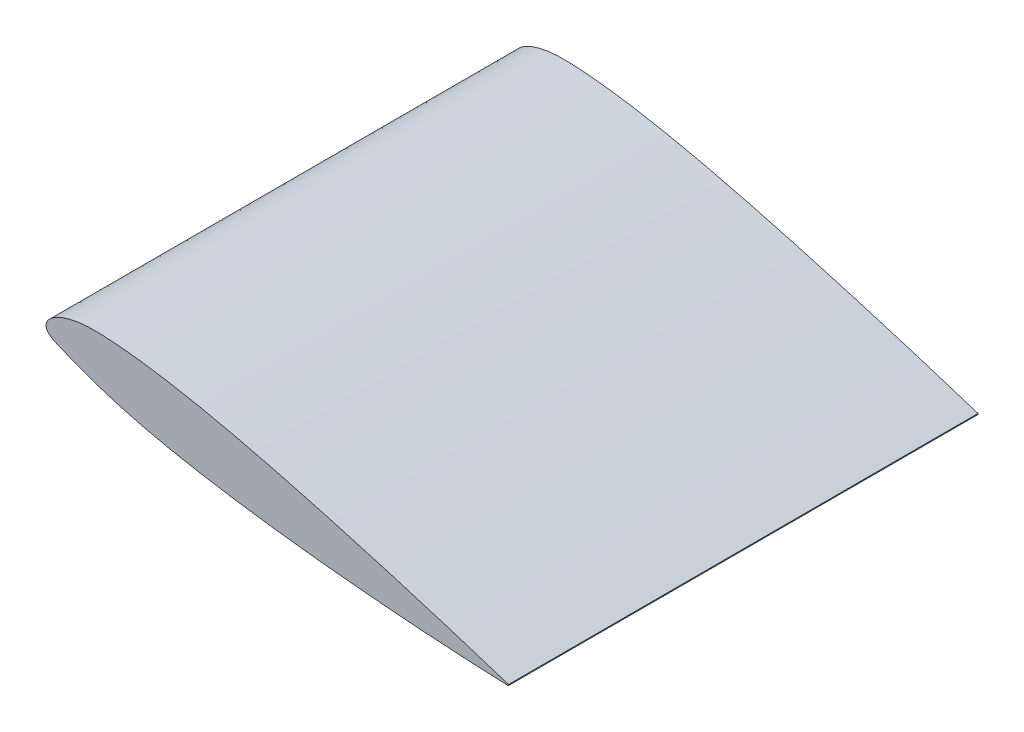
SolidWorks part; units mm, degrees
ref_plane "Płaszczyzna przednia"
ref_plane "Płaszczyzna górna" through (0, 0, 0) normal (0, 1, 0) x (1, 0, 0)
ref_plane "Płaszczyzna prawa" through (0, 0, 0) normal (1, 0, 0) x (0, 0, -1)
curve "Krzywa3"
  spline degree 3 poles (1, 0.0013, 0) (0.9998, 0.0013, 0) (0.9989, 0.0014, 0) (0.9968, 0.0017, 0) (0.9934, 0.0022, 0) (0.9886, 0.0029, 0) (0.9826, 0.0038, 0) (0.9751, 0.0049, 0) (0.9664, 0.0061, 0) (0.9564, 0.0076, 0) (0.9452, 0.0092, 0) (0.9327, 0.0109, 0) (0.9191, 0.0128, 0) (0.9043, 0.0148, 0) (0.8884, 0.017, 0) (0.8714, 0.0192, 0) (0.8535, 0.0216, 0) (0.8346, 0.0241, 0) (0.8147, 0.0266, 0) (0.794, 0.0292, 0) (0.7725, 0.0318, 0) (0.7503, 0.0345, 0) (0.7273, 0.0373, 0) (0.7038, 0.04, 0) (0.6797, 0.0427, 0) (0.6551, 0.0454, 0) (0.6301, 0.0481, 0) (0.6047, 0.0508, 0) (0.5791, 0.0533, 0) (0.5532, 0.0558, 0) (0.5272, 0.0582, 0) (0.5011, 0.0605, 0) (0.475, 0.0626, 0) (0.449, 0.0646, 0) (0.4231, 0.0664, 0) (0.3975, 0.068, 0) (0.3721, 0.0694, 0) (0.347, 0.0706, 0) (0.3224, 0.0715, 0) (0.2982, 0.0722, 0) (0.2746, 0.0726, 0) (0.2516, 0.0727, 0) (0.2293, 0.0725, 0) (0.2078, 0.072, 0) (0.187, 0.0713, 0) (0.1671, 0.0702, 0) (0.148, 0.0689, 0) (0.1298, 0.0672, 0) (0.1123, 0.0653, 0) (0.0953, 0.0628, 0) (0.0792, 0.0596, 0) (0.064, 0.0557, 0) (0.0502, 0.051, 0) (0.0378, 0.0457, 0) (0.027, 0.0399, 0) (0.018, 0.0338, 0) (0.0107, 0.0276, 0) (0.0052, 0.0214, 0) (0.0014, 0.0155, 0) (-0.0008, 0.0099, 0) (-0.0014, 0.0047, 0) (-0.0002, -0.0001, 0) (0.0023, -0.0042, 0) (0.0062, -0.0076, 0) (0.0111, -0.0104, 0) (0.017, -0.0128, 0) (0.0238, -0.0149, 0) (0.0314, -0.0168, 0) (0.0399, -0.0186, 0) (0.0492, -0.0205, 0) (0.0594, -0.0225, 0) (0.0706, -0.0247, 0) (0.0828, -0.027, 0) (0.0963, -0.0296, 0) (0.1112, -0.0323, 0) (0.1277, -0.035, 0) (0.1455, -0.0374, 0) (0.1644, -0.0397, 0) (0.1843, -0.0417, 0) (0.205, -0.0435, 0) (0.2265, -0.045, 0) (0.2488, -0.0462, 0) (0.2718, -0.0472, 0) (0.2954, -0.0479, 0) (0.3196, -0.0484, 0) (0.3443, -0.0486, 0) (0.3694, -0.0486, 0) (0.3948, -0.0484, 0) (0.4206, -0.0479, 0) (0.4466, -0.0473, 0) (0.4727, -0.0464, 0) (0.4989, -0.0454, 0) (0.5251, -0.0442, 0) (0.5512, -0.0429, 0) (0.5772, -0.0415, 0) (0.603, -0.0399, 0) (0.6285, -0.0382, 0) (0.6536, -0.0364, 0) (0.6784, -0.0346, 0) (0.7026, -0.0327, 0) (0.7262, -0.0307, 0) (0.7493, -0.0287, 0) (0.7716, -0.0267, 0) (0.7932, -0.0247, 0) (0.814, -0.0227, 0) (0.834, -0.0207, 0) (0.853, -0.0187, 0) (0.871, -0.0168, 0) (0.888, -0.0149, 0) (0.904, -0.0131, 0) (0.9188, -0.0114, 0) (0.9325, -0.0098, 0) (0.945, -0.0083, 0) (0.9563, -0.0069, 0) (0.9663, -0.0056, 0) (0.9751, -0.0045, 0) (0.9825, -0.0036, 0) (0.9886, -0.0028, 0) (0.9934, -0.0021, 0) (0.9968, -0.0017, 0) (0.9988, -0.0014, 0) (0.9998, -0.0013, 0) (1, -0.0013, 0) knots 0 0 0 0 0.000339 0.001354 0.003042 0.0054 0.008419 0.012092 0.016408 0.021354 0.026917 0.033081 0.039829 0.047141 0.054998 0.063377 0.072255 0.081607 0.091408 0.101629 0.112244 0.123222 0.134533 0.146147 0.15803 0.170151 0.182475 0.19497 0.2076 0.220332 0.233129 0.245957 0.258782 0.271567 0.284279 0.296882 0.309343 0.321628 0.333704 0.34554 0.357105 0.368367 0.379298 0.389869 0.400055 0.40983 0.419169 0.428054 0.436681 0.445097 0.45319 0.460863 0.468035 0.474639 0.480626 0.485963 0.490636 0.494656 0.49806 0.500929 0.503404 0.505691 0.507977 0.510416 0.513148 0.516239 0.519714 0.523574 0.527822 0.532466 0.537535 0.543075 0.549152 0.555845 0.563238 0.571416 0.580295 0.589636 0.599413 0.609602 0.620179 0.631116 0.642386 0.65396 0.665807 0.677897 0.690197 0.702675 0.715296 0.728027 0.740833 0.75368 0.766531 0.779352 0.792108 0.804762 0.817281 0.829629 0.841773 0.853679 0.865313 0.876645 0.887642 0.898273 0.908511 0.918326 0.92769 0.936579 0.944968 0.952833 0.960152 0.966905 0.973073 0.978639 0.983588 0.987905 0.991579 0.994599 0.996957 0.998646 0.999661 1 1 1 1
sketch "Szkic1" plane through (0, 0, 0) normal (0, 0, 1) x (1, 0, 0)
  line L0 (492.5145, -86.2046) -> (492.2942, -87.4437)
  line L1 (492.4044, -86.8242) -> (0, 0) construction
  line L2 (6.0112, 33.8097) -> (498.291, -53.7153) construction
  line L3 (6.0112, 33.8097) -> (-4.5337, -25.4997) construction
  line L4 (-4.5337, -25.4997) -> (487.7461, -113.0247) construction
  line L5 (498.291, -53.7153) -> (487.7461, -113.0247) construction
  line L6 (0, 0) -> (-27.8525, 4.9111) construction
  line L7 (0, 0) -> (-37.2129, 0) construction
  spline S1 degree 3 poles (492.5145, -86.2046) (469.1525, -78.5836) (429.1915, -65.9555) (373.7979, -49.2132) (325.4436, -35.1387) (281.0231, -22.7915) (239.3268, -11.8733) (201.8626, -2.7476) (169.2002, 4.432) (141.6822, 9.7711) (119.4336, 13.5527) (101.6773, 16.0714) (88.2073, 17.639) (78.7303, 18.5718) (69.6253, 19.2804) (60.8216, 19.7953) (52.2732, 20.0029) (44.0475, 19.802) (36.2689, 19.137) (29.0564, 17.9973) (22.5157, 16.4146) (16.7329, 14.4537) (11.7698, 12.201) (7.6619, 9.7514) (4.4205, 7.1953) (2.037, 4.6063) (0.4937, 2.0314) (-0.2101, -0.5087) (-0.0581, -2.9466) (0.869, -5.1858) (2.4753, -7.181) (4.6559, -8.9734) (7.3531, -10.635) (10.5239, -12.2283) (14.1326, -13.8104) (18.155, -15.4333) (22.5842, -17.1436) (27.435, -18.982) (34.8756, -21.7848) (43.0608, -24.8537) (52.1233, -28.1367) (59.9863, -30.8443) (75.0178, -35.6125) (94.6072, -40.9771) (122.9238, -47.6188) (153.965, -53.8418) (190.7613, -60.0599) (228.9856, -65.5651) (271.8352, -70.8847) (317.7715, -75.7295) (368.0257, -80.1796) (420.2509, -83.9719) (461.6838, -86.2293) (486.2562, -87.2212) (491.834, -87.4269) (492.2942, -87.4437) knots 0 0 0 0 0.072255 0.123222 0.170151 0.220332 0.258782 0.296882 0.333704 0.357105 0.379298 0.400055 0.40983 0.419169 0.428054 0.436681 0.445097 0.45319 0.460863 0.468035 0.474639 0.480626 0.485963 0.490636 0.494656 0.49806 0.500929 0.503404 0.505691 0.507977 0.510416 0.513148 0.516239 0.519714 0.523574 0.527822 0.532466 0.537535 0.543075 0.555845 0.563238 0.571416 0.580295 0.609602 0.631116 0.665807 0.702675 0.740833 0.779352 0.829629 0.876645 0.92769 0.983588 0.998646 1 1 1 1
  dimension "D3" = 500
  dimension "D1" = 90
  dimension "D2" = 90
  dimension "D4" = 90
  dimension "D5" = 90
  dimension "D6" = 10
extrude "Dodanie-wyciągnięcie1" add sketch "Szkic1" along normal blind 500 contours S1 L0
equation "\"kat natarcia\"= 10"
equation "\"D6@Szkic1\"= \"kat natarcia\""
